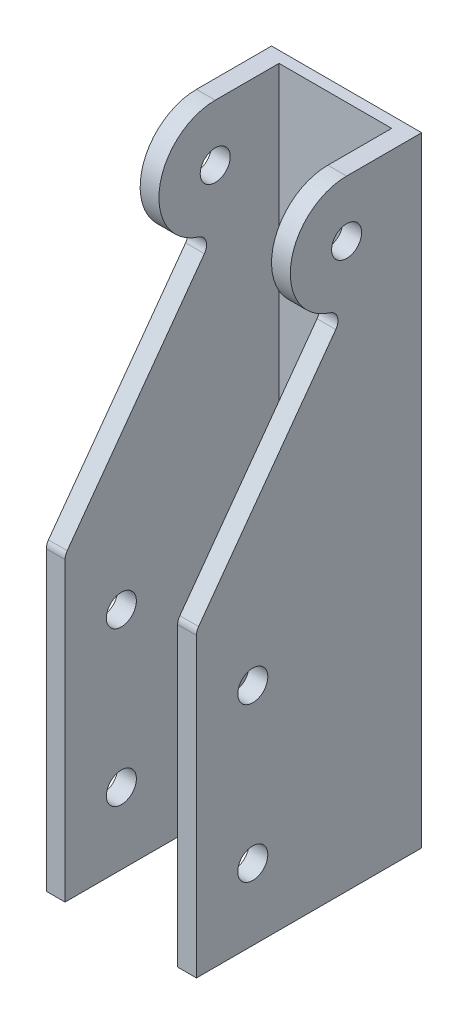
SolidWorks part; units mm, degrees
ref_plane "Front Plane" through (0, 0, 0) normal (1, 0, 0) x (0, 1, 0)
ref_plane "Top Plane" through (0, 0, 0) normal (0, 0, 1) x (0, 1, 0)
ref_plane "Right Plane" through (0, 0, 0) normal (0, 1, 0) x (-1, 0, 0)
sketch "Sketch1" plane through (0, 0, 0) normal (0, 0, 1) x (0, 1, 0)
  line L0 (-100, 0) -> (100, 0) construction
  line L1 (-100, -20) -> (100, -20)
  line L2 (-100, 20) -> (100, 20)
  line L3 (-100, 20) -> (-100, -20)
  line L4 (100, 20) -> (100, -20)
  point P4 (0, 0)
  point P13 (-97, 12)
  dimension "D3" = 200
  dimension "D1" = 20
  dimension "D2" = 20
extrude "Boss-Extrude1" add sketch "Sketch1" along normal blind 3
sketch "Sketch2" plane through (0, 0, 3) normal (0, 0, 1) x (1, 0, 0)
  line L0 (-20, 100) -> (-15, 100)
  line L1 (20, 100) -> (-20, 100) construction
  line L2 (-15, 100) -> (-15, -100)
  line L3 (-20, -100) -> (20, -100) construction
  line L4 (-15, -100) -> (-20, -100)
  line L5 (-20, -100) -> (-20, 100)
  line L6 (0, -100) -> (0, 100) construction
  line L7 (15, -100) -> (20, -100)
  line L8 (20, 100) -> (15, 100)
  line L9 (20, -100) -> (20, 100)
  line L10 (15, 100) -> (15, -100)
  point P5 (-17.5, 100)
  point P14 (0, 0)
  point P18 (17.5, 100)
  dimension "D1" = 5
extrude "Boss-Extrude2" add sketch "Sketch2" along normal blind 60
sketch "Sketch4" plane through (-20, 0, 0) normal (-1, 0, 0) x (0, -1, 0)
  line L0 (-100, 0) -> (-85, 0)
  line L1 (-100, 0) -> (100, 0) construction
  line L2 (-100, 63) -> (-100, 0) construction
  line L3 (-85, 0) -> (-85, 20) construction
  line L4 (-100, 20) -> (-89, 20) construction
  line L5 (5, 0) -> (5, 45) construction
  line L6 (46, 0) -> (46, 45) construction
  line L7 (5, 45) -> (46, 45) construction
  line L8 (5, 49) -> (46, 49) construction
  line L9 (-15, 60) -> (65, 60)
  line L10 (-15, 0) -> (-15, 60) construction
  line L11 (65, 60) -> (65, 0)
  line L12 (-100, 20) -> (-100, 0)
  line L13 (-70, 20) -> (-15, 60)
  line L14 (-85, 0) -> (65, 0)
  circle A0 centre (-85, 20) radius 4
  arc A1 (-70, 20) -> (-100, 20) centre (-85, 20) ccw
  circle A2 centre (5, 45) radius 4
  circle A3 centre (46, 45) radius 4
  circle A4 centre (-85, 20) radius 15 construction
  point P14 (-70, 15)
  point P21 (-67.2661, 12.4817)
  point P26 (-12.2661, 32.4817)
  point P28 (-23, 0)
  point P29 (-23, 40)
  point P30 (-85, 8)
  point P31 (65, 8)
  point P35 (-79.5906, 8)
  dimension "D3" = 8
  dimension "D9" = 8
  dimension "D1" = 15
  dimension "D2" = 20
  dimension "D5" = 41
  dimension "D6" = 45
  dimension "D7" = 45
  dimension "D8" = 70
  dimension "D12" = 60
  dimension "D13" = 20
  dimension "80" = 80
  dimension "D4" = 11
extrude "Cut-Extrude1" cut sketch "Sketch4" against normal blind 60
fillet "Fillet2" radius 3 4 edges at (17.5, 70, 20) (17.5, 15, 60) (-17.5, 15, 60) (-17.5, 70, 20)
